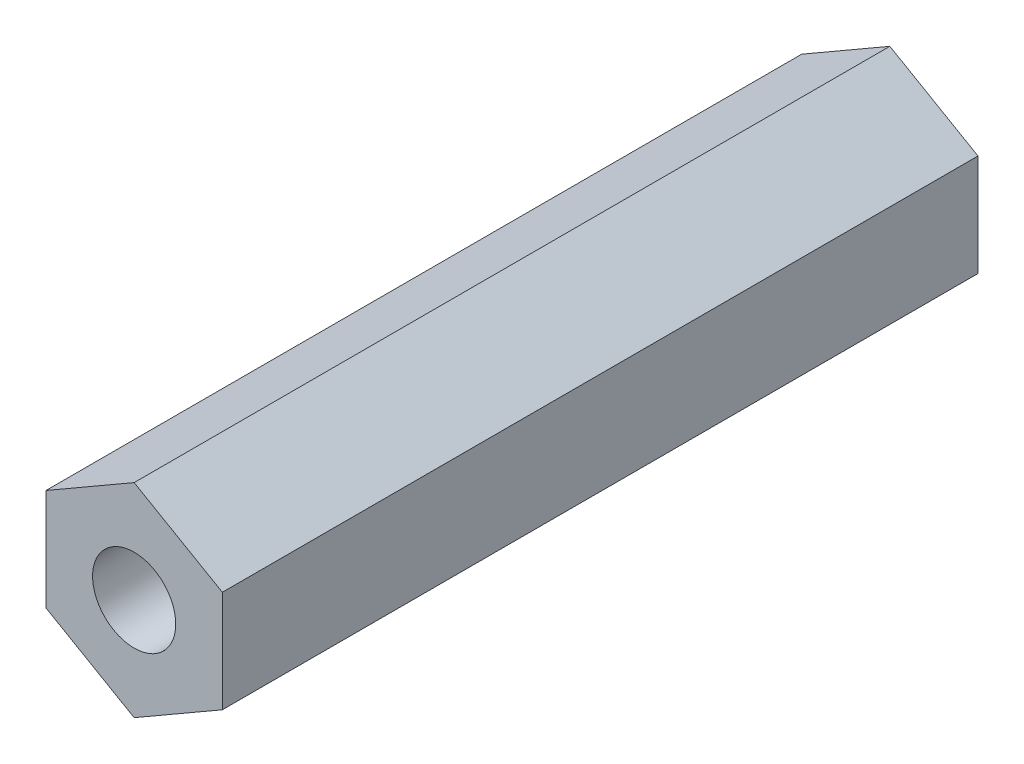
SolidWorks part; units mm, degrees
ref_plane "前视基准面" through (0, 0, 0) normal (0, 0, 1) x (1, 0, 0)
ref_plane "上视基准面" through (0, 0, 0) normal (0, 1, 0) x (1, 0, 0)
ref_plane "右视基准面" through (0, 0, 0) normal (1, 0, 0) x (0, 0, -1)
other "Configuration Table"
sketch "Profile_1" plane through (0, 0, 0) normal (0, 0, 1) x (1, 0, 0)
  line L0 (3.5, 2.0207) -> (0, 4.0415)
  line L1 (0, 4.0415) -> (-3.5, 2.0207)
  line L2 (-3.5, 2.0207) -> (-3.5, -2.0207)
  line L3 (-3.5, -2.0207) -> (0, -4.0415)
  line L4 (0, -4.0415) -> (3.5, -2.0207)
  line L5 (3.5, -2.0207) -> (3.5, 2.0207)
  circle A0 centre (0, 0) radius 1.65
extrude "Hex_standoff" add sketch "Profile_1" along normal blind 30 from offset 0
